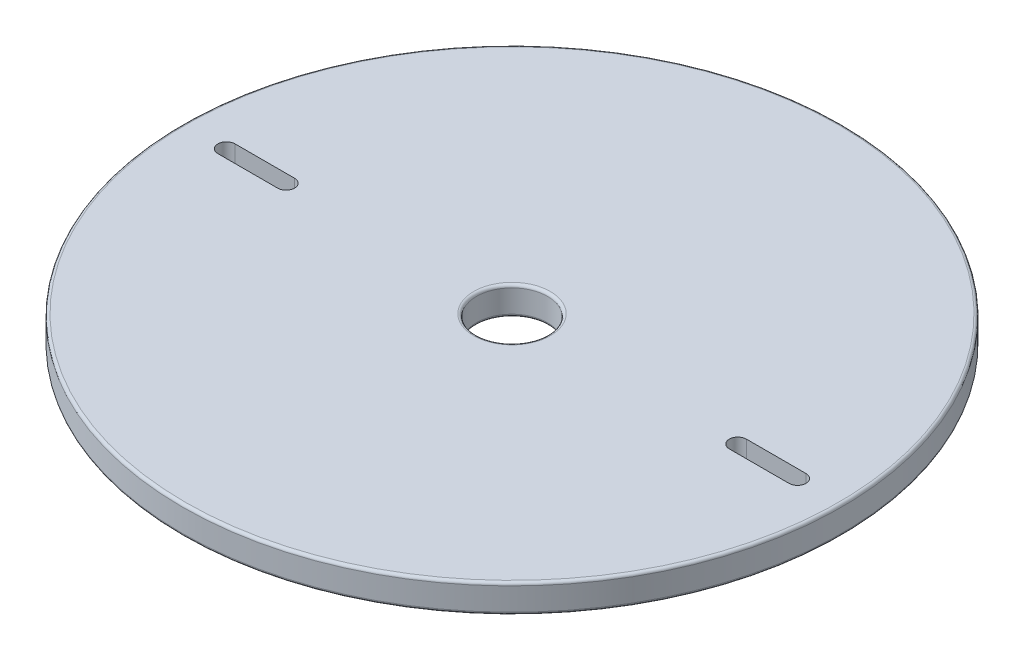
SolidWorks part; units mm, degrees
material "FR4 Fiberglass"
ref_plane "Front Plane" through (0, 0, 0) normal (0, 0, 1) x (1, 0, 0)
ref_plane "Top Plane" through (0, 0, 0) normal (0, 1, 0) x (1, 0, 0)
ref_plane "Right Plane" through (0, 0, 0) normal (1, 0, 0) x (0, 0, -1)
sketch "Sketch1" plane through (0, 0, 0) normal (0, 1, 0) x (1, 0, 0)
  circle A0 centre (0, 0) radius 11.6
  dimension "D1" = 23.2
extrude "Boss-Extrude1" add sketch "Sketch1" along normal mid plane 1
sketch "Sketch2" plane through (0, 0.5, 0) normal (0, 1, 0) x (1, 0, 0)
  line L0 (-10.05, 0) -> (-7.95, 0) construction
  line L1 (-10.05, 0.3) -> (-7.95, 0.3)
  line L2 (-10.05, -0.3) -> (-7.95, -0.3)
  arc A0 (-10.05, 0.3) -> (-10.05, -0.3) centre (-10.05, 0) ccw
  arc A1 (-7.95, -0.3) -> (-7.95, 0.3) centre (-7.95, 0) ccw
  point P2 (-9, 0)
  dimension "D1" = 2.1
  dimension "D2" = 0.3
  dimension "D3" = 9
extrude "Cut-Extrude1" cut sketch "Sketch2" against normal up to next
mirror "Mirror1" about plane through (0, 0, 0) normal (1, 0, 0) of "Cut-Extrude1"
sketch "Sketch3" plane through (0, 0.5, 0) normal (0, 1, 0) x (1, 0, 0)
  circle A0 centre (0, 0) radius 1.25
  dimension "D1" = 2.5
extrude "Cut-Extrude2" cut sketch "Sketch3" against normal up to next
fillet "Fillet1" radius 0.1 4 edges at (0, -0.5, 11.6) (0, 0.5, 11.6) (0, -0.5, 1.25) (0, 0.5, 1.25)
